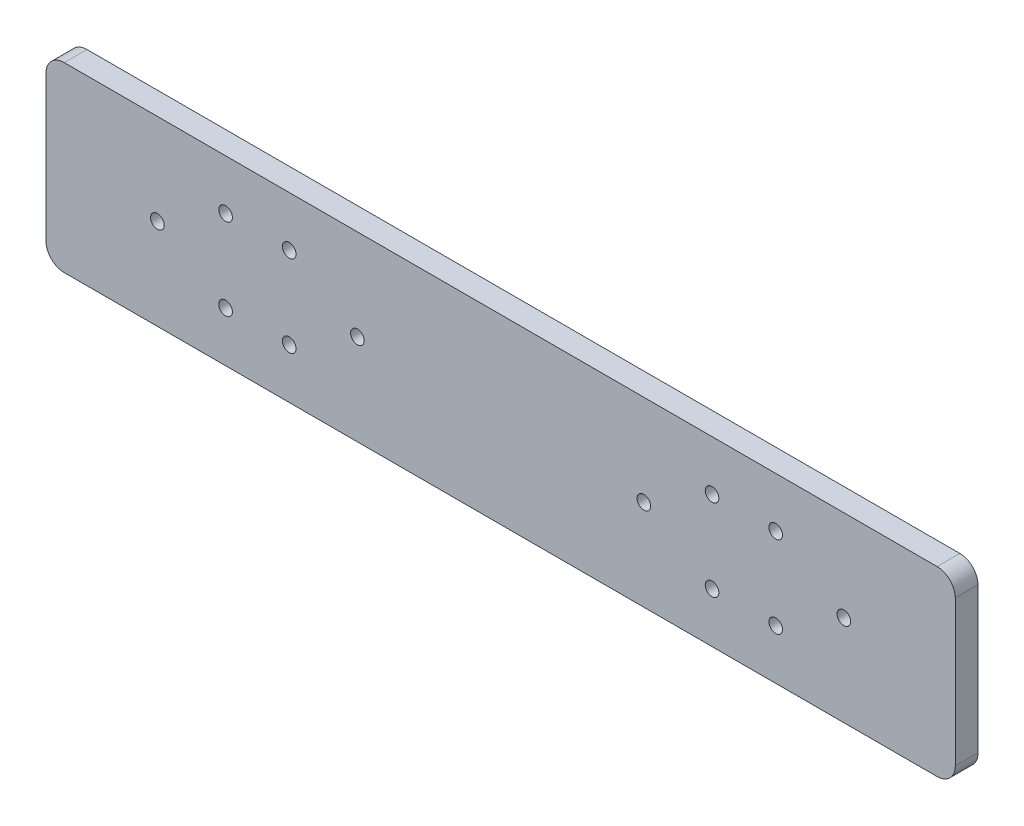
SolidWorks part; units mm, degrees
ref_plane "Plan de face" through (0, 0, 0) normal (0, 0, 1) x (1, 0, 0)
ref_plane "Plan de dessus" through (0, 0, 0) normal (0, 1, 0) x (1, 0, 0)
ref_plane "Plan de droite" through (0, 0, 0) normal (1, 0, 0) x (0, 0, -1)
sketch "Esquisse1" plane through (0, 0, 0) normal (0, 0, 1) x (1, 0, 0)
  line L1 (0, 0) -> (200, 0)
  line L2 (0, 0) -> (0, 40)
  line L3 (0, 40) -> (200, 40)
  line L4 (200, 0) -> (200, 40)
  dimension "D1" = 200
  dimension "D2" = 40
extrude "Boss.-Extru.1" add sketch "Esquisse1" against normal blind 5
sketch "Esquisse3" plane through (0, 0, -5) normal (0, 0, -1) x (-1, 0, 0)
  line L5 (0, 0) -> (-200, 0) construction
  line L6 (-117.5, 0) -> (-82.5, 0)
  line L7 (-117.5, 0) -> (-82.5, 0)
  line L9 (-117.5, 0) -> (-117.5, 5)
  line L10 (-117.5, 0) -> (-82.5, 0)
  line L11 (-117.5, 0) -> (-117.5, 5)
  line L12 (-117.5, 5) -> (-82.5, 5)
  line L13 (-82.5, 0) -> (-82.5, 5)
  line L14 (-117.5, 5) -> (-82.5, 5)
  line L15 (-82.5, 0) -> (-82.5, 5)
  dimension "D1" = 35
  dimension "D4" = 35
  dimension "D5" = 5
sketch "Esquisse5" plane through (0, 0, -5) normal (0, 0, -1) x (-1, 0, 0)
  line L1 (-117.5, 0) -> (-82.5, 0)
  line L2 (-117.5, 0) -> (-117.5, 5)
  line L3 (-117.5, 5) -> (-82.5, 5)
  line L4 (-82.5, 0) -> (-82.5, 5)
extrude "Boss.-Extru.3" add sketch "Esquisse5" along normal blind 35
sketch "Esquisse6" plane through (0, 5, 0) normal (0, 1, 0) x (1, 0, 0)
  circle A0 centre (86.5678, 36) radius 2.5
  circle A1 centre (113.5678, 36.0006) radius 2.5
  circle A2 centre (113.5678, 9.0006) radius 2.5
  circle A3 centre (86.5, 9.0006) radius 2.5
extrude "Enlèv. mat.-Extru.2" cut sketch "Esquisse6" against normal blind 35 contours A1 | A0 | A3 | A2
sketch "Esquisse9" plane through (0, 0, 0) normal (0, 0, 1) x (1, 0, 0)
  line L0 (0, 0) -> (100, 0)
  line L1 (117.5, 0) -> (82.5, 0) construction
  line L2 (100, 0) -> (100, 40)
  line L3 (200, 40) -> (0, 40) construction
  line L4 (100, 40) -> (100, 20)
  line L5 (70, 20) -> (68.5, 20)
  line L6 (100, 20) -> (128, 20)
  line L7 (128, 20) -> (128, 7.5)
  line L8 (128, 20) -> (128, 32.5)
  line L10 (179, 32.5) -> (179, 7.5)
  line L12 (162, 11) -> (179, 11)
  line L13 (162, 29) -> (160.5, 29)
  line L14 (162, 11) -> (160.5, 11)
  line L15 (128, 7.5) -> (179, 7.5)
  line L16 (128, 20) -> (130, 20)
  line L17 (38, 29) -> (21, 29)
  line L18 (72, 20) -> (70, 20)
  line L20 (72, 7.5) -> (21, 7.5)
  line L21 (38, 11) -> (39.5, 11)
  line L33 (162, 29) -> (179, 29)
  line L34 (130, 20) -> (131.5, 20)
  line L35 (38, 29) -> (39.5, 29)
  line L36 (38, 11) -> (21, 11)
  line L37 (21, 32.5) -> (21, 7.5)
  line L38 (72, 20) -> (72, 32.5)
  line L39 (72, 20) -> (72, 7.5)
  line L40 (21, 7.5) -> (46.5, 7.5)
  line L41 (46.5, 7.5) -> (46.5, 32.5)
  line L42 (153.5, 7.5) -> (153.5, 32.5)
  circle A9 centre (160.5, 11) radius 1.5
  circle A10 centre (160.5, 29) radius 1.5
  circle A11 centre (131.5, 20) radius 1.5
  circle A12 centre (68.5, 20) radius 1.5
  circle A13 centre (39.5, 29) radius 1.5
  circle A14 centre (39.5, 11) radius 1.5
  circle A15 centre (24.5, 20) radius 1.5
  circle A16 centre (53.5, 11) radius 1.5
  circle A17 centre (53.5, 29) radius 1.5
  circle A18 centre (175.5, 20) radius 1.5
  circle A19 centre (146.5, 11) radius 1.5
  circle A20 centre (146.5, 29) radius 1.5
  dimension "D9" = 28
  dimension "D1" = 51
  dimension "D2" = 12.5
  dimension "D3" = 12.5
  dimension "D4" = 25
  dimension "D5" = 17
  dimension "D6" = 17
  dimension "D7" = 1.5
  dimension "D8" = 2
  dimension "D10" = 1.5
  dimension "D11" = 1.5
extrude "Enlèv. mat.-Extru.3" cut sketch "Esquisse9" against normal blind 35 contours A9 | A10 | A14 | A12 | A13 | A11 | A15 | A16 | A19 | A18 | A20 | A17
fillet "Congé2" radius 4 6 edges at (82.5, 2.5, -40) (117.5, 2.5, -40) (200, 40, -2.5) (200, 0, -2.5) (0, 0, -2.5) (0, 40, -2.5)
sketch "Esquisse11" plane through (0, 5, 0) normal (0, 1, 0) x (1, 0, 0)
  line L0 (83.6716, 38.8284) -> (83.6716, 5)
  line L1 (117.5, 5) -> (82.5, 5) construction
  line L2 (83.6716, 38.8284) -> (116.3284, 38.8284)
  line L3 (116.3284, 38.8284) -> (116.3284, 5)
  line L4 (116.3284, 5) -> (83.6716, 5)
  arc A0 (86.5, 40) -> (82.5, 36) centre (86.5, 36) ccw construction
  arc A1 (117.5, 36) -> (113.5, 40) centre (113.5, 36) ccw construction
extrude "Boss.-Extru.4" add sketch "Esquisse11" against normal blind 5
sketch "Esquisse12" plane through (0, 5, 0) normal (0, 1, 0) x (1, 0, 0)
sketch "Esquisse13" plane through (0, 5, 0) normal (0, 1, 0) x (1, 0, 0)
sketch "Esquisse14" plane through (0, 5, 0) normal (0, 1, 0) x (1, 0, 0)
  circle A1 centre (99.935, 22.565) radius 6.5
  circle A2 centre (99.935, 32.565) radius 1.75
  circle A3 centre (107.0061, 29.636) radius 1.75
  circle A4 centre (109.935, 22.565) radius 1.75
  circle A5 centre (107.0061, 15.4939) radius 1.75
  circle A6 centre (99.935, 12.565) radius 1.75
  circle A7 centre (92.864, 15.4939) radius 1.75
  circle A8 centre (89.935, 22.565) radius 1.75
  circle A9 centre (92.864, 29.636) radius 1.75
  circle A10 centre (113.3701, 36) radius 1.75
  circle A11 centre (113.3701, 9.1299) radius 1.75
  circle A12 centre (86.5, 36) radius 1.75
  circle A13 centre (86.5, 9.1299) radius 1.75
extrude "Enlèv. mat.-Extru.4" cut sketch "Esquisse14" against normal blind 5
